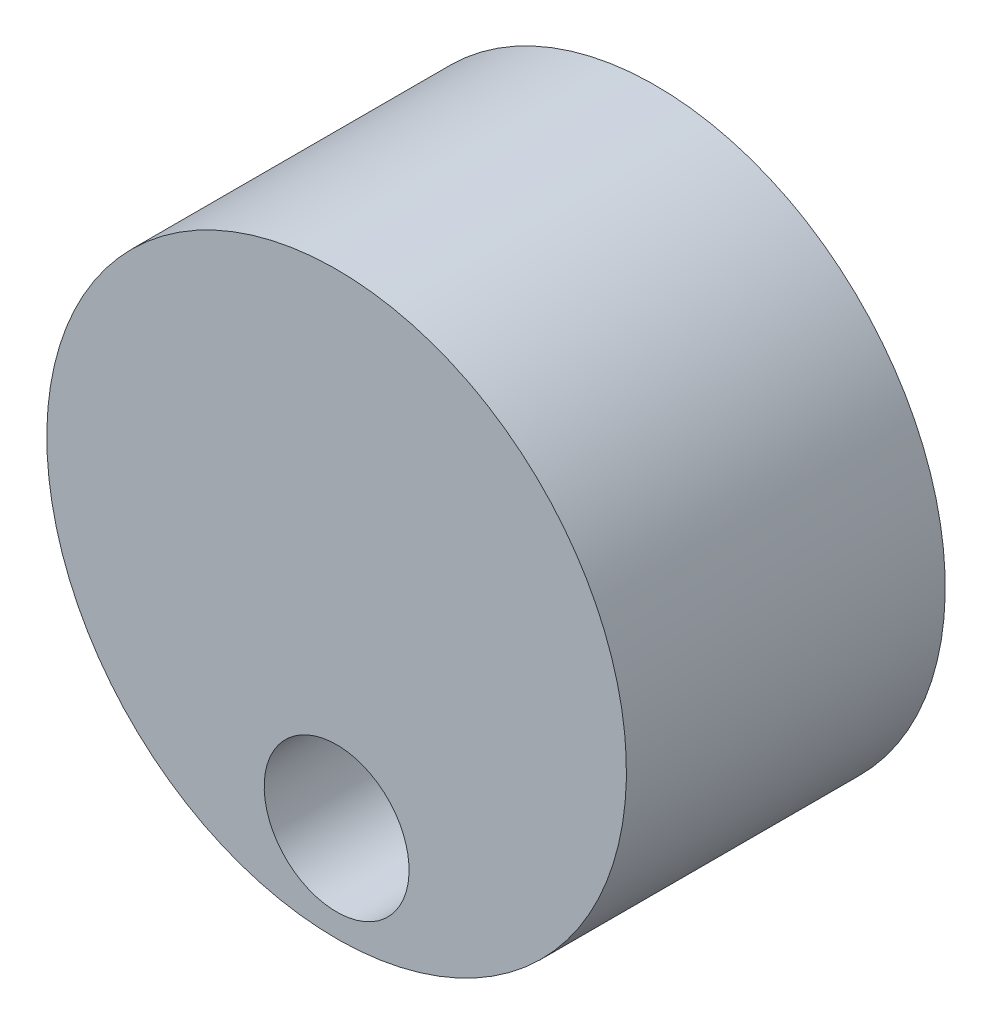
SolidWorks part; units mm, degrees
ref_plane "Plan de face" through (0, 0, 0) normal (0, 0, 1) x (1, 0, 0)
ref_plane "Plan de dessus" through (0, 0, 0) normal (0, 1, 0) x (1, 0, 0)
ref_plane "Plan de droite" through (0, 0, 0) normal (1, 0, 0) x (0, 0, -1)
sketch "Esquisse1" plane through (0, 0, 0) normal (0, 0, 1) x (1, 0, 0)
  line L0 (0, 0) -> (0, -8.509) construction
  ellipse E0 centre (0, 0) end of major axis (5.758, 11.3197) minor radius 12.7
  ellipse E1 centre (0, -8.509) end of major axis (-1.7944, -5.8897) minor radius 3.175
extrude "Boss.-Extru.1" add sketch "Esquisse1" along normal blind 13.97
